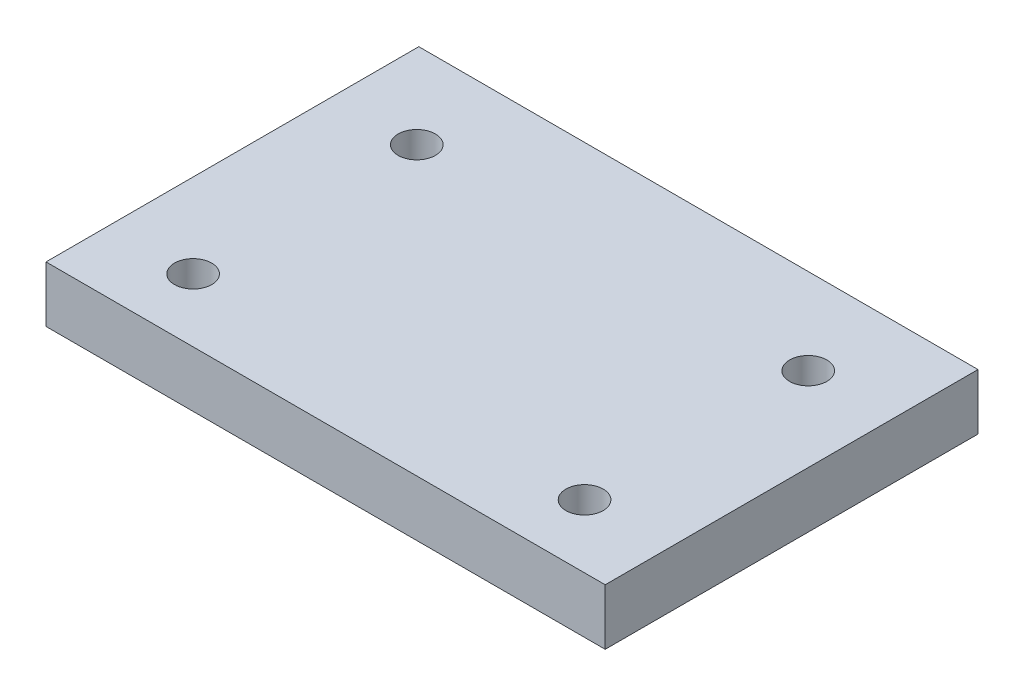
SolidWorks part; units mm, degrees
ref_plane "Front Plane" through (0, 0, 0) normal (0, 0, 1) x (1, 0, 0)
ref_plane "Top Plane" through (0, 0, 0) normal (0, 1, 0) x (1, 0, 0)
ref_plane "Right Plane" through (0, 0, 0) normal (1, 0, 0) x (0, 0, -1)
sketch "Sketch1" plane through (0, 0, 0) normal (0, 1, 0) x (1, 0, 0)
  line L5 (0, 0) -> (30, 0)
  line L6 (0, 0) -> (0, 20)
  line L7 (0, 20) -> (30, 20)
  line L8 (30, 0) -> (30, 20)
  circle A0 centre (4.5, 3.3921) radius 1
  circle A1 centre (25.5, 3.3921) radius 1
  circle A2 centre (25.5, 15.3921) radius 1
  circle A3 centre (4.5, 15.3921) radius 1
  point P13 (4.5, 15.3921)
  dimension "D3" = 2
  dimension "D5" = 2
  dimension "D1" = 30
  dimension "D2" = 20
  dimension "D4" = 21
  dimension "D6" = 4.5
  dimension "D7" = 12
extrude "Boss-Extrude2" add sketch "Sketch1" along normal blind 3
